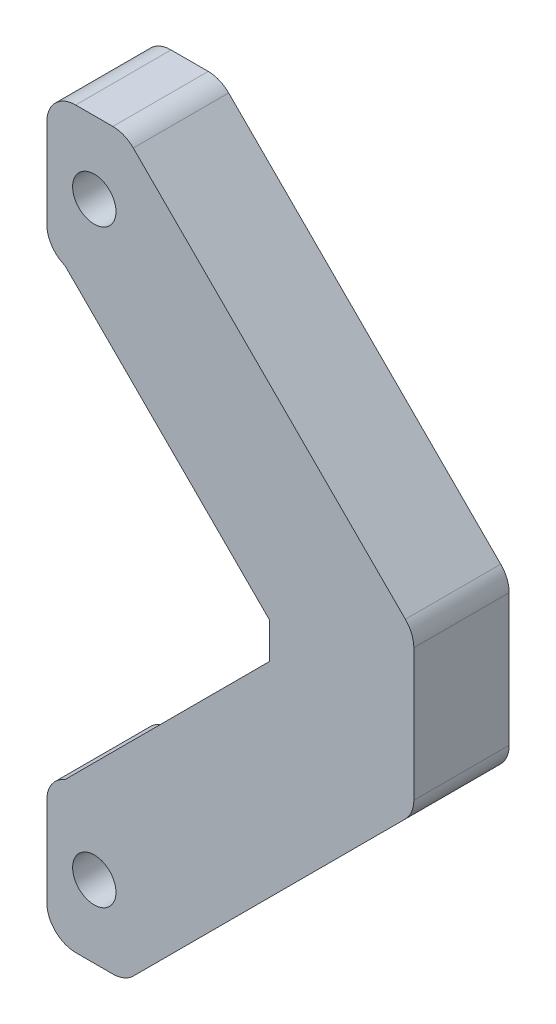
SolidWorks part; units mm, degrees
ref_plane "Front Plane" through (0, 0, 0) normal (0, 0, 1) x (1, 0, 0)
ref_plane "Top Plane" through (0, 0, 0) normal (0, 1, 0) x (1, 0, 0)
ref_plane "Right Plane" through (0, 0, 0) normal (1, 0, 0) x (0, 0, -1)
sketch "Model" plane through (0, 0, 0) normal (0, 0, 1) x (1, 0, 0)
  line L0 (12.1142, 5.9858) -> (-6.7142, 24.8142)
  line L1 (-6.7142, -24.8142) -> (12.1142, -5.9858)
  line L2 (-11.4421, -15.4) -> (2.7, -1.2579)
  line L3 (2.7, -1.2579) -> (2.7, 1.2579)
  line L4 (2.7, 1.2579) -> (-11.4421, 15.4)
  line L5 (-10.7, -25.4) -> (-8.1284, -25.4)
  line L6 (-12.7, 23.4) -> (-12.7, 17.2572)
  line L7 (-8.1284, 25.4) -> (-10.7, 25.4)
  line L8 (12.7, -4.5716) -> (12.7, 4.5716)
  line L9 (-12.7, -17.2572) -> (-12.7, -23.4)
  circle A0 centre (-9.4142, 20.4) radius 1.5
  circle A1 centre (-9.4142, -20.4) radius 1.5
  arc A2 (-6.7142, 24.8142) -> (-8.1284, 25.4) centre (-8.1284, 23.4) ccw
  arc A3 (12.7, 4.5716) -> (12.1142, 5.9858) centre (10.7, 4.5716) ccw
  arc A4 (12.1142, -5.9858) -> (12.7, -4.5716) centre (10.7, -4.5716) ccw
  arc A5 (-8.1284, -25.4) -> (-6.7142, -24.8142) centre (-8.1284, -23.4) ccw
  arc A6 (-12.7, -23.4) -> (-10.7, -25.4) centre (-10.7, -23.4) ccw
  arc A7 (-11.4421, -15.4) -> (-12.7, -17.2572) centre (-10.7, -17.2572) ccw
  arc A8 (-12.7, 17.2572) -> (-11.4421, 15.4) centre (-10.7, 17.2572) ccw
  arc A9 (-10.7, 25.4) -> (-12.7, 23.4) centre (-10.7, 23.4) ccw
extrude "Boss-Extrude1" add sketch "Model" along normal blind 6.6
